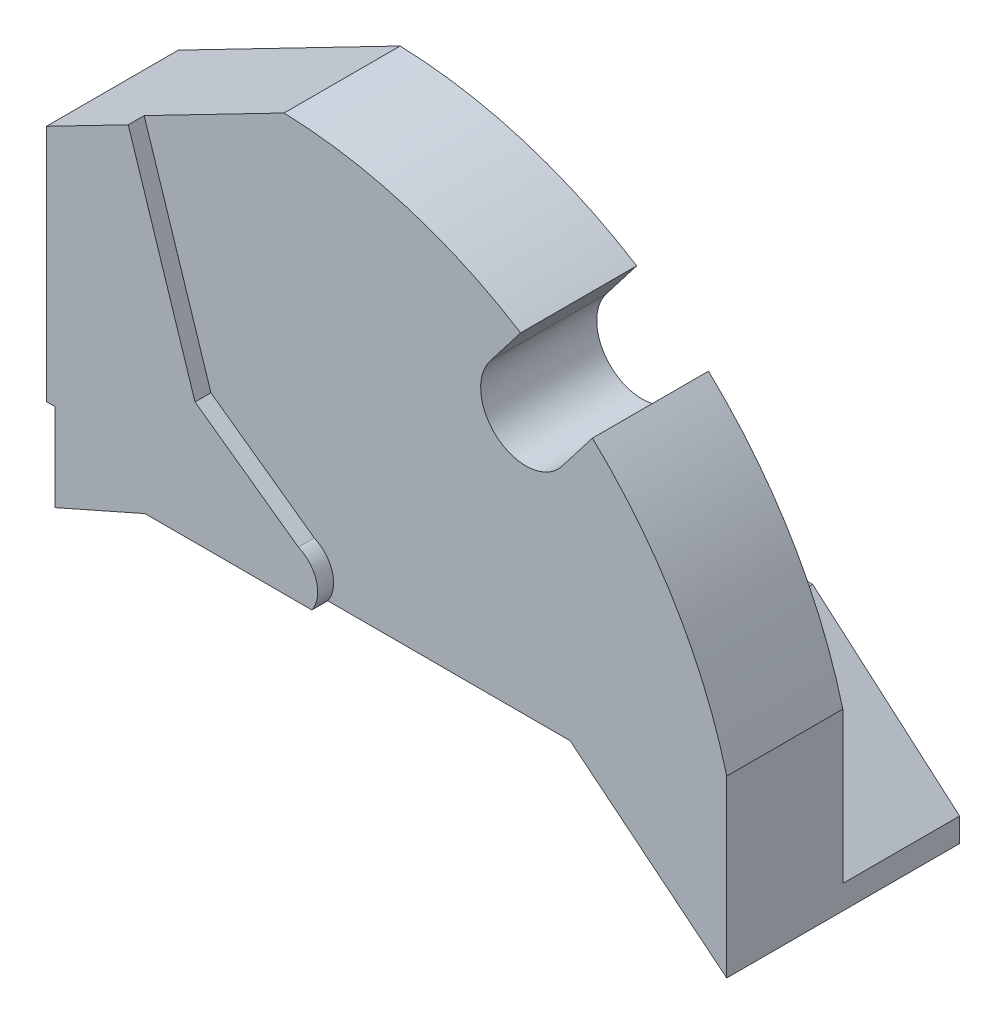
SolidWorks part; units mm, degrees
ref_plane "Piano frontale" through (0, 0, 0) normal (0, 0, 1) x (1, 0, 0)
ref_plane "Piano superiore" through (0, 0, 0) normal (0, 1, 0) x (1, 0, 0)
ref_plane "Piano destro" through (0, 0, 0) normal (1, 0, 0) x (0, 0, -1)
sketch "Schizzo1" plane through (0, 0, 0) normal (0, 0, 1) x (1, 0, 0)
  line L0 (0, 0) -> (0, 30)
  line L1 (0, 30) -> (27.9027, 44.4014)
  line L2 (0, 0) -> (1.1, 0)
  line L3 (0, 30) -> (27.9027, 30) construction
  line L4 (27.9027, 30) -> (27.9027, 44.4014) construction
  line L5 (1.1, 0) -> (1.1, -6)
  line L6 (1.1, -6) -> (83.6, -6)
  line L7 (83.6, -6) -> (83.6, 0)
  line L8 (83.6, 0) -> (66.7, 0) construction
  line L9 (66.7, 0) -> (66.7, 28.3696) construction
  line L10 (66.7, 28.3696) -> (57.6691, 35.3268) construction
  line L11 (66.0294, 36.8389) -> (58.3398, 26.8575) construction
  line L12 (70.5448, 33.3603) -> (62.8552, 23.3788)
  line L13 (61.5139, 40.3176) -> (53.8243, 30.3361)
  arc A0 (27.9027, 44.4014) -> (83.6, 0) centre (26.0383, -15.0715) cw
  arc A1 (70.5448, 33.3603) -> (61.5139, 40.3176) centre (66.0294, 36.8389) ccw
  arc A2 (53.8243, 30.3361) -> (62.8552, 23.3788) centre (58.3398, 26.8575) ccw
  point P15 (62.1846, 31.8482)
  point P20 (54.8611, 22.342)
  dimension "D5" = 14.4014
  dimension "D8" = 59.5021
  dimension "D13" = 12
  dimension "D1" = 30
  dimension "D2" = 1.1
  dimension "D3" = 6
  dimension "D4" = 31.4
  dimension "D6" = 82.5
  dimension "D7" = 6
  dimension "D9" = 16.9
  dimension "D10" = 28.3696
  dimension "D11" = 11.4
  dimension "D12" = 11.4
extrude "Estrusione-Estrusione1" add sketch "Schizzo1" along normal blind 14.6 contours A2 L13 A0 L1 L0 L2 L5 L6 L7 L12
sketch "Schizzo2" plane through (0, 0, 0) normal (0, 0, -1) x (-1, 0, 0)
  line L0 (-1.1, -3) -> (-65.1, -3)
  line L1 (-1.1, 0) -> (-1.1, -6) construction
  line L2 (-65.1, -3) -> (-65.1, -6)
  line L3 (-1.1, -6) -> (-83.6, -6) construction
  line L4 (-65.1, -6) -> (-1.1, -6)
  line L5 (-1.1, -6) -> (-1.1, -3)
  dimension "D1" = 3
  dimension "D2" = 64
extrude "Estrusione-Estrusione2" add sketch "Schizzo2" along normal blind 14.7
sketch "Schizzo4" plane through (0, 0, 14.6) normal (0, 0, 1) x (1, 0, 0)
  line L0 (1.1, -6) -> (12.4, -6)
  line L1 (1.1, -6) -> (83.6, -6) construction
  line L2 (12.4, -6) -> (1.1, -11)
  line L3 (1.1, -11) -> (1.1, -6)
  dimension "D1" = 11.3
  dimension "D2" = 5
extrude "Estrusione-Estrusione3" add sketch "Schizzo4" against normal blind 11.3
sketch "Schizzo5" plane through (0, 0, 3.3) normal (0, 0, -1) x (-1, 0, 0)
  line L0 (-1.1, -6) -> (-33.8, -6)
  line L1 (-33.8, -6) -> (-1.1, -19)
  line L2 (-1.1, -19) -> (-1.1, -6)
  dimension "D1" = 32.7
  dimension "D2" = 13
extrude "Estrusione-Estrusione4" add sketch "Schizzo5" along normal blind 14.9
sketch "Schizzo6" plane through (0, -6, 0) normal (0, -1, 0) x (1, 0, 0)
  line L0 (1.1, -11.6) -> (65.1, -11.6)
  line L1 (65.1, -14.7) -> (65.1, 0) construction
  line L2 (65.1, -11.6) -> (65.1, -14.7)
  line L3 (65.1, -14.7) -> (1.1, -14.7)
  line L4 (1.1, -14.7) -> (1.1, -11.6)
extrude "Estrusione-Estrusione5" add sketch "Schizzo6" along normal blind 13
sketch "Schizzo7" plane through (65.1, 0, 0) normal (1, 0, 0) x (0, 0, -1)
  line L0 (14.7, -19) -> (14.7, -22.05)
  line L1 (14.7, -22.05) -> (11.6, -19)
  line L2 (11.6, -19) -> (14.7, -19)
  dimension "D1" = 3.05
extrude "Estrusione-Estrusione8" add sketch "Schizzo7" against normal up to vertex
sketch "Schizzo9" plane through (0, 0, 0) normal (0, 0, 1) x (1, 0, 0)
  line L0 (83.6, -6) -> (65.1, -6)
  line L1 (65.1, -6) -> (83.6, -22)
  line L2 (83.6, -22) -> (83.6, -6)
  dimension "D1" = 16
extrude "Estrusione-Estrusione9" add sketch "Schizzo9" along normal up to vertex (14.6 mm away)
sketch "Schizzo16" plane through (0, 0, 0) normal (0, 0, -1) x (-1, 0, 0)
  line L0 (-65.1, -3) -> (-83.6, -19)
  line L1 (-83.6, -22) -> (-83.6, 0) construction
  line L2 (-83.6, -19) -> (-83.6, -22)
  line L3 (-83.6, -22) -> (-65.1, -6)
  line L4 (-65.1, -6) -> (-65.1, -3)
extrude "Estrusione-Estrusione13" add sketch "Schizzo16" along normal up to vertex (14.7 mm away)
sketch "Schizzo17" plane through (0, 0, -14.7) normal (0, 0, -1) x (-1, 0, 0)
  line L0 (-65.1, -6) -> (-65.1, -22.05)
  line L1 (-65.1, -22.05) -> (-83.6, -22)
  line L2 (-83.6, -22) -> (-65.1, -6)
extrude "Estrusione-Estrusione14" add sketch "Schizzo17" against normal up to vertex
sketch "Schizzo18" plane through (65.1, 0, 0) normal (-1, 0, 0) x (0, 0, 1)
  line L3 (-11.6, -22.05) -> (-11.6, -19)
  line L4 (-11.6, -19) -> (-14.7, -22.05)
  line L5 (-14.7, -22.05) -> (-11.6, -22.05)
  line L6 (-11.6, -22.05) -> (-11.6, -19)
  line L7 (-11.6, -19) -> (-14.7, -22.05)
  line L8 (-14.7, -22.05) -> (-11.6, -22.05)
  dimension "D1" = 0
extrude "Taglio-Estrusione3" cut sketch "Schizzo18" against normal blind 15
sketch "Schizzo19" plane through (0, 0, 14.6) normal (0, 0, 1) x (1, 0, 0)
  line L0 (0, 30) -> (10.3, 35.3161)
  line L1 (0, 30) -> (27.9027, 44.4014) construction
  line L2 (10.3, 35.3161) -> (18.7, 9.3161)
  line L3 (18.7, 9.3161) -> (31.7, 0)
  line L4 (18.7, 9.3161) -> (0, 9.3161) construction
  line L5 (0, 0) -> (0, 30) construction
  line L6 (10.3, 35.3161) -> (10.3, 9.3161) construction
  line L7 (0, 30) -> (0, 0)
  line L8 (0, 0) -> (1.1, 0)
  line L9 (1.1, 0) -> (1.1, -11)
  line L10 (1.1, -11) -> (12.4, -6)
  line L11 (12.4, -6) -> (33.4, -6)
  line L12 (12.4, -6) -> (65.1, -6) construction
  arc A0 (31.7, 0) -> (33.4, -6) centre (30.1394, -3.683) cw
  dimension "D7" = 4
  dimension "D1" = 26
  dimension "D2" = 10.3
  dimension "D3" = 8.4
  dimension "D4" = 6
  dimension "D5" = 21
  dimension "D6" = 13
sketch "Schizzo20" plane through (80.1, 0, 0) normal (-1, 0, 0) x (0, 0, 1)
  line L3 (-11.6, -22.0095) -> (-11.6, -19)
  line L4 (-11.6, -19) -> (-14.6588, -22.0095)
  line L5 (-14.6588, -22.0095) -> (-11.6, -22.0095)
  line L6 (-11.6, -22.0095) -> (-11.6, -19)
  line L7 (-11.6, -19) -> (-14.6588, -22.0095)
  line L8 (-14.6588, -22.0095) -> (-11.6, -22.0095)
  dimension "D1" = 0
extrude "Taglio-Estrusione4" cut sketch "Schizzo20" against normal up to surface (0.0312 mm away)
sketch "Schizzo22" plane through (0, 0, -14.7) normal (0, 0, -1) x (-1, 0, 0)
  line L8 (-65.1, -6) -> (-62.6823, -6)
  line L9 (-65.1, -6) -> (-33.8, -6) construction
  line L10 (-62.6823, -6) -> (-83.6, -22)
  line L11 (-83.6, -22) -> (-65.1, -6)
sketch "Schizzo23" plane through (0, 0, 14.6) normal (0, 0, 1) x (1, 0, 0)
  line L0 (65.1, -6) -> (83.6, -22)
  line L4 (83.6, -22) -> (63.8912, -6)
  line L6 (65.1, -6) -> (62.6823, -6) construction
  line L7 (63.8912, -6) -> (65.1, -6)
loft "Loft3" add profiles "Schizzo22", "Schizzo23"
extrude "Estrusione-Estrusione15" add sketch "Schizzo19" along normal blind 2
